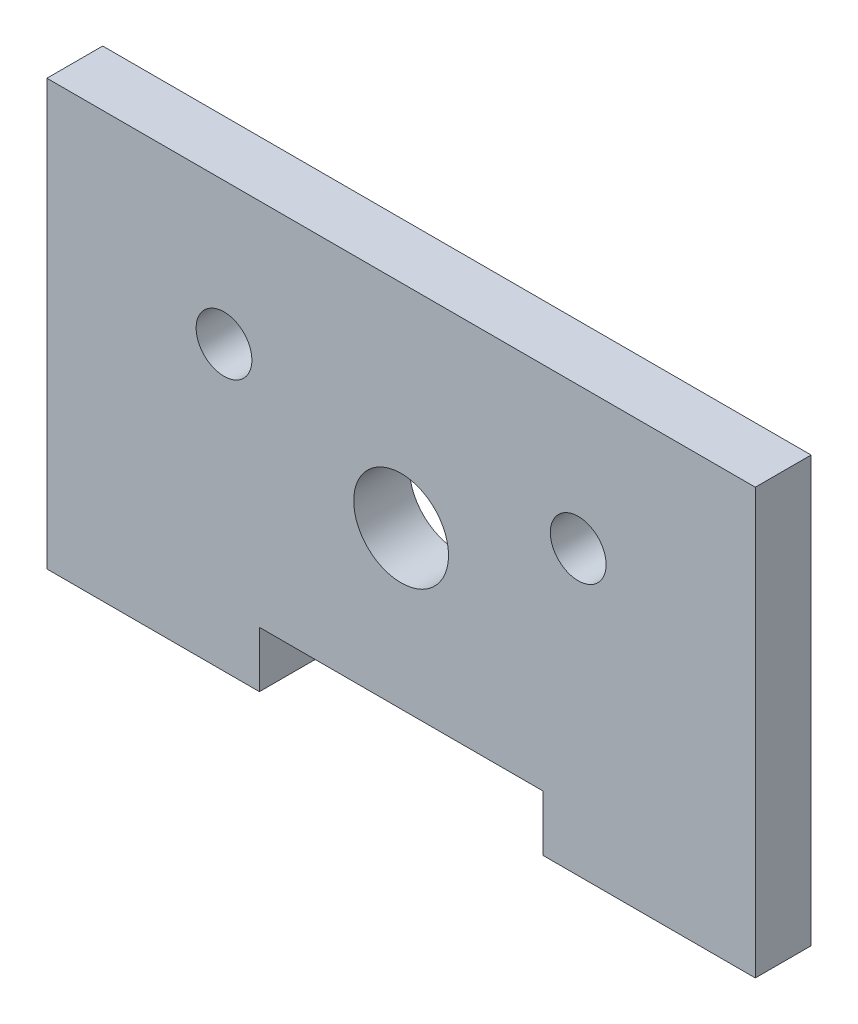
SolidWorks part; units mm, degrees
material "Acrylic (Medium-high impact)"
ref_plane "Front Plane" through (0, 0, 0) normal (0, 0, 1) x (1, 0, 0)
ref_plane "Top Plane" through (0, 0, 0) normal (0, 1, 0) x (1, 0, 0)
ref_plane "Right Plane" through (0, 0, 0) normal (1, 0, 0) x (0, 0, -1)
sketch "Sketch1" plane through (0, 0, 0) normal (0, 0, 1) x (1, 0, 0)
  line L0 (-63.5, -38.1) -> (-25.4, -38.1)
  line L1 (-63.5, 38.1) -> (63.5, 38.1)
  line L4 (63.5, 38.1) -> (63.5, -38.1)
  line L5 (0, 46.5667) -> (0, -57.542) construction
  line L6 (63.5, -38.1) -> (25.4, -38.1)
  line L7 (-25.4, -38.1) -> (-25.4, -28.1)
  line L8 (-25.4, -28.1) -> (25.4, -28.1)
  line L9 (-63.5, -38.1) -> (-63.5, 38.1)
  line L10 (25.4, -38.1) -> (25.4, -28.1)
  circle A0 centre (0, 0) radius 8.5
  circle A1 centre (-31.75, 12.7) radius 5
  circle A2 centre (31.75, 12.7) radius 5
  point P0 (0, 0)
  point P12 (-31.75, -38.1)
  point P14 (31.75, -38.1)
  point P22 (0, -28.1)
  dimension "D6" = 50.8
  dimension "D1" = 76.2
  dimension "D2" = 127
  dimension "D3" = 38.1
  dimension "D4" = 25.4
  dimension "D5" = 10
extrude "Boss-Extrude1" add sketch "Sketch1" along normal blind 10
